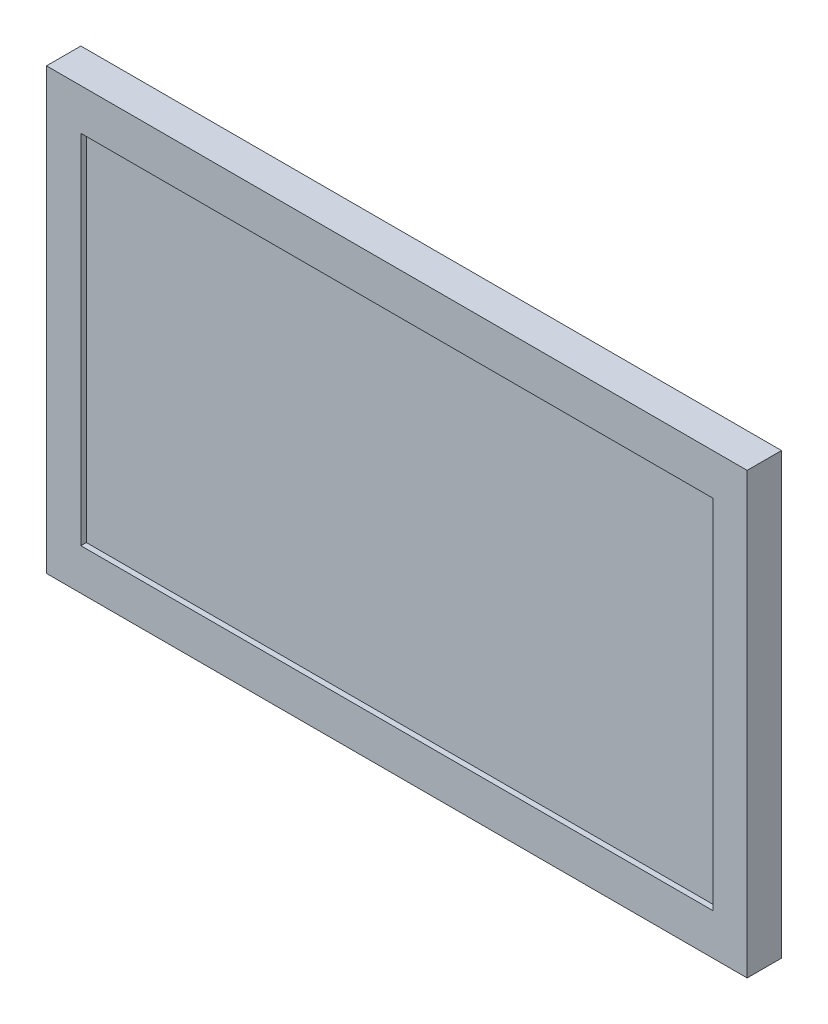
SolidWorks part; units mm, degrees
ref_plane "Front Plane" through (0, 0, 0) normal (0, 0, 1) x (1, 0, 0)
ref_plane "Top Plane" through (0, 0, 0) normal (0, 1, 0) x (1, 0, 0)
ref_plane "Right Plane" through (0, 0, 0) normal (1, 0, 0) x (0, 0, -1)
sketch "Sketch1" plane through (0, 0, 0) normal (0, 0, 1) x (1, 0, 0)
  line L1 (-161.925, -101.6) -> (161.925, -101.6)
  line L2 (-161.925, -101.6) -> (-161.925, 101.6)
  line L3 (-161.925, 101.6) -> (161.925, 101.6)
  line L4 (161.925, -101.6) -> (161.925, 101.6)
  line L5 (-161.925, -101.6) -> (161.925, 101.6) construction
  line L6 (-161.925, 101.6) -> (161.925, -101.6) construction
  point P0 (0, 0)
  dimension "D1" = 323.85
  dimension "D2" = 203.2
extrude "Boss-Extrude1" add sketch "Sketch1" along normal blind 15.875
sketch "Sketch2" plane through (0, 0, 15.875) normal (0, 0, 1) x (1, 0, 0)
  line L1 (-146.05, -82.55) -> (146.05, -82.55)
  line L2 (-146.05, -82.55) -> (-146.05, 82.55)
  line L3 (-146.05, 82.55) -> (146.05, 82.55)
  line L4 (146.05, -82.55) -> (146.05, 82.55)
  line L5 (-146.05, -82.55) -> (146.05, 82.55) construction
  line L6 (-146.05, 82.55) -> (146.05, -82.55) construction
  point P0 (0, 0)
  dimension "D1" = 165.1
  dimension "D2" = 292.1
extrude "Cut-Extrude1" cut sketch "Sketch2" against normal blind 2.54
sketch "Sketch3" plane through (0, 0, 0) normal (0, 0, -1) x (-1, 0, 0)
  line L1 (-37.5, -37.5) -> (37.5, -37.5) construction
  line L2 (-37.5, -37.5) -> (-37.5, 37.5) construction
  line L3 (-37.5, 37.5) -> (37.5, 37.5) construction
  line L4 (37.5, -37.5) -> (37.5, 37.5) construction
  line L5 (-37.5, -37.5) -> (37.5, 37.5) construction
  line L6 (-37.5, 37.5) -> (37.5, -37.5) construction
  circle A0 centre (-37.5, 37.5) radius 2.3749
  circle A1 centre (37.5, 37.5) radius 2.3749
  circle A2 centre (37.5, -37.5) radius 2.3749
  circle A3 centre (-37.5, -37.5) radius 2.3749
  point P0 (0, 0)
  dimension "D3" = 4.7498
  dimension "D4" = 4.7498
  dimension "D5" = 4.7498
  dimension "D6" = 4.7498
  dimension "D1" = 75
  dimension "D2" = 75
extrude "Cut-Extrude2" cut sketch "Sketch3" against normal blind 2.54
